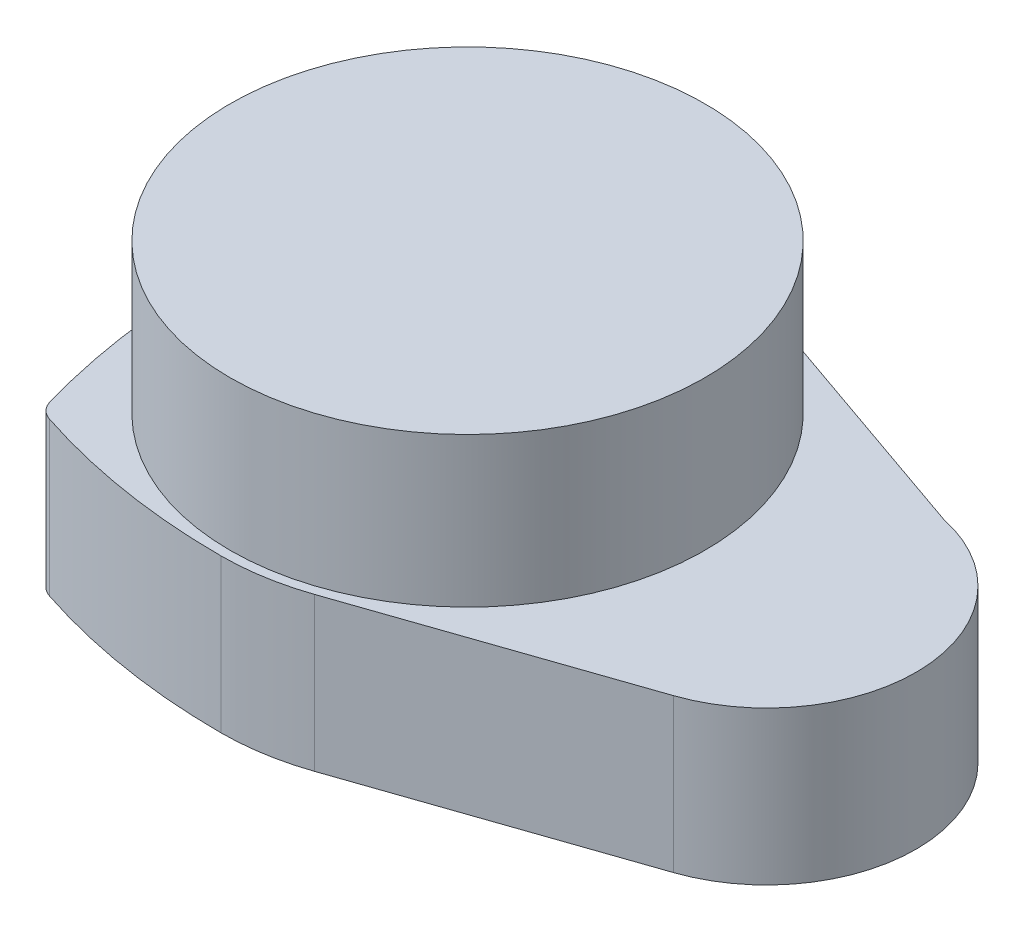
SolidWorks part; units mm, degrees
ref_plane "前视基准面" through (0, 0, 0) normal (0, 0, 1) x (1, 0, 0)
ref_plane "上视基准面" through (0, 0, 0) normal (0, 1, 0) x (1, 0, 0)
ref_plane "右视基准面" through (0, 0, 0) normal (1, 0, 0) x (0, 0, -1)
other "Configuration Table"
sketch "草图1" plane through (0, 0, 0) normal (0, 1, 0) x (1, 0, 0)
  circle A0 centre (0, 0) radius 31.75
  point P3 (0, 0)
  dimension "D1" = 63.5
extrude "凸台-拉伸2" add sketch "草图1" along normal blind 20 contours A0
sketch "草图3" plane through (0, 0, 0) normal (0, -1, 0) x (1, 0, 0)
  line L0 (0, 0) -> (-5.8272, 0) construction
  line L2 (46.5, 18.9143) -> (10.725, 31.2086)
  line L3 (44.1464, -19.5655) -> (11.8544, -30.7973)
  arc A0 (10.725, 31.2086) -> (0, 33) centre (0, 0) ccw
  arc A1 (44.1464, -19.5655) -> (46.5, 18.9143) centre (40, 0) ccw
  arc A2 (0, -33) -> (11.8544, -30.7973) centre (0, 0) ccw
  arc A4 (-28.8135, 28.1049) -> (-28.8135, -28.1049) centre (63.4292, 0) ccw
  arc A5 (0, -33) -> (-28.8135, -28.1049) centre (0, 54.2476) cw
  arc A6 (0, 33) -> (-28.8135, 28.1049) centre (0, -54.2476) ccw
  point P0 (-25, 33)
  point P4 (-25, -33)
  point P5 (0, -54.2476)
  point P7 (40, 0)
  point P17 (63.4292, 0)
  dimension "D3" = 40
  dimension "D4" = 40
  dimension "D5" = 66
  dimension "D1" = 33
  dimension "D2" = 25
extrude "凸台-拉伸5" add sketch "草图3" along normal blind 20.5 contours A1 L2 A0 A6 A4 A5 A2 L3
fillet "圆角1" radius 3 2 edges at (-28.8135, -10.25, -28.1049) (-28.8135, -10.25, 28.1049)
